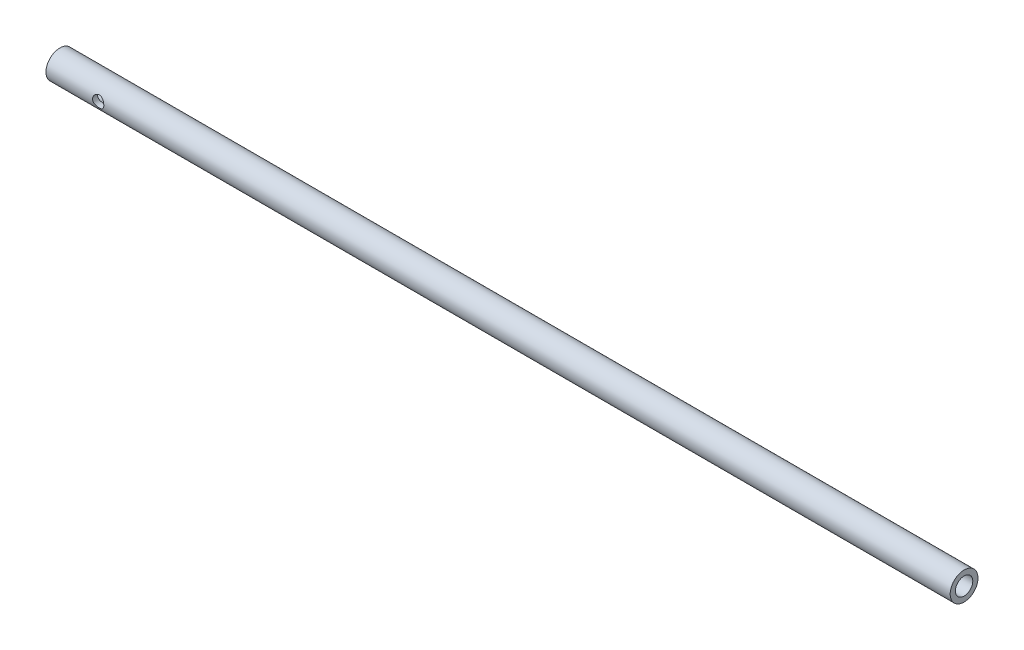
SolidWorks part; units mm, degrees
ref_plane "Front Plane" through (0, 0, 0) normal (0, 0, 1) x (1, 0, 0)
ref_plane "Top Plane" through (0, 0, 0) normal (0, 1, 0) x (1, 0, 0)
ref_plane "Right Plane" through (0, 0, 0) normal (1, 0, 0) x (0, 0, -1)
sketch "Sketch1" plane through (0, 0, 0) normal (1, 0, 0) x (0, 0, -1)
  circle A0 centre (0, 0) radius 16
  circle A1 centre (0, 0) radius 10
  dimension "D1" = 32
  dimension "D2" = 20
extrude "Boss-Extrude1" add sketch "Sketch1" against normal blind 1040
sketch "Sketch2" plane through (0, 0, 0) normal (0, 0, 1) x (1, 0, 0)
  line L0 (-1040, 16) -> (-1040, -16) construction
  line L1 (-1040, 0) -> (-604.8317, 0) construction
  circle A0 centre (-980, 0) radius 6.5
  dimension "D1" = 13
  dimension "D2" = 60
extrude "Cut-Extrude1" cut sketch "Sketch2" against normal mid plane 59
